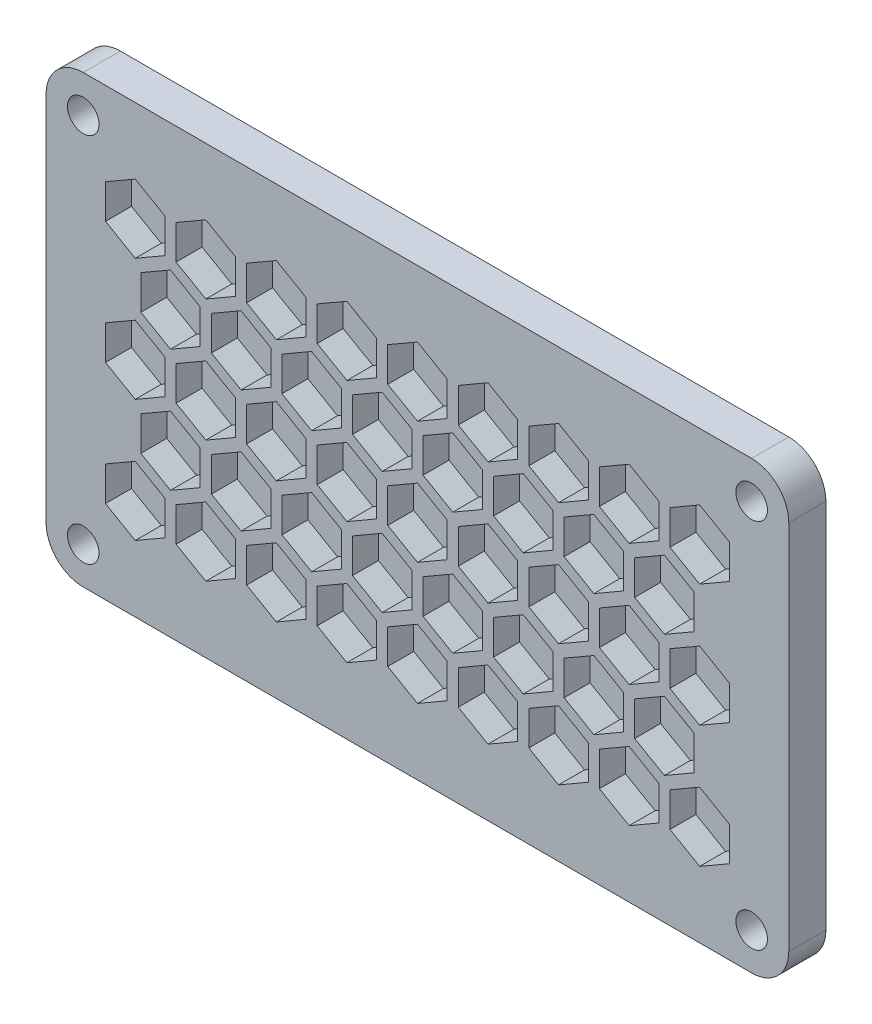
SolidWorks part; units mm, degrees
ref_plane "前视基准面" through (0, 0, 0) normal (0, 0, 1) x (1, 0, 0)
ref_plane "上视基准面" through (0, 0, 0) normal (0, 1, 0) x (1, 0, 0)
ref_plane "右视基准面" through (0, 0, 0) normal (1, 0, 0) x (0, 0, -1)
sketch "草图1" plane through (0, 0, 0) normal (0, 0, 1) x (1, 0, 0)
  line L0 (-90, -60) -> (90, -60)
  line L1 (100, -50) -> (100, 50)
  line L2 (90, 60) -> (-90, 60)
  line L3 (-100, 50) -> (-100, -50)
  arc A0 (-100, -50) -> (-90, -60) centre (-90, -50) ccw
  arc A1 (90, -60) -> (100, -50) centre (90, -50) ccw
  arc A2 (100, 50) -> (90, 60) centre (90, 50) ccw
  arc A3 (-90, 60) -> (-100, 50) centre (-90, 50) ccw
extrude "凸台-拉伸1" add sketch "草图1" along normal blind 10
ref_plane "基准面1" through (0, 0, 10) normal (0, 0, 1) x (1, 0, 0)
sketch "草图2" plane through (0, 0, 10) normal (0, 0, 1) x (1, 0, 0)
  line L0 (0, 9.2376) -> (-8, 4.6188)
  line L1 (-8, 4.6188) -> (-8, -4.6188)
  line L2 (-8, -4.6188) -> (0, -9.2376)
  line L3 (0, -9.2376) -> (8, -4.6188)
  line L4 (8, -4.6188) -> (8, 4.6188)
  line L5 (8, 4.6188) -> (0, 9.2376)
  line L6 (19, 9.2376) -> (11, 4.6188)
  line L7 (11, 4.6188) -> (11, -4.6188)
  line L8 (11, -4.6188) -> (19, -9.2376)
  line L9 (19, -9.2376) -> (27, -4.6188)
  line L10 (27, -4.6188) -> (27, 4.6188)
  line L11 (27, 4.6188) -> (19, 9.2376)
  line L12 (-19, 9.2376) -> (-27, 4.6188)
  line L13 (-27, 4.6188) -> (-27, -4.6188)
  line L14 (-27, -4.6188) -> (-19, -9.2376)
  line L15 (-19, -9.2376) -> (-11, -4.6188)
  line L16 (-11, -4.6188) -> (-11, 4.6188)
  line L17 (-11, 4.6188) -> (-19, 9.2376)
  line L18 (38, 9.2376) -> (30, 4.6188)
  line L19 (30, 4.6188) -> (30, -4.6188)
  line L20 (30, -4.6188) -> (38, -9.2376)
  line L21 (38, -9.2376) -> (46, -4.6188)
  line L22 (46, -4.6188) -> (46, 4.6188)
  line L23 (46, 4.6188) -> (38, 9.2376)
  line L24 (-38, 9.2376) -> (-46, 4.6188)
  line L25 (-46, 4.6188) -> (-46, -4.6188)
  line L26 (-46, -4.6188) -> (-38, -9.2376)
  line L27 (-38, -9.2376) -> (-30, -4.6188)
  line L28 (-30, -4.6188) -> (-30, 4.6188)
  line L29 (-30, 4.6188) -> (-38, 9.2376)
  line L30 (57, 9.2376) -> (49, 4.6188)
  line L31 (49, 4.6188) -> (49, -4.6188)
  line L32 (49, -4.6188) -> (57, -9.2376)
  line L33 (57, -9.2376) -> (65, -4.6188)
  line L34 (65, -4.6188) -> (65, 4.6188)
  line L35 (65, 4.6188) -> (57, 9.2376)
  line L36 (-57, 9.2376) -> (-65, 4.6188)
  line L37 (-65, 4.6188) -> (-65, -4.6188)
  line L38 (-65, -4.6188) -> (-57, -9.2376)
  line L39 (-57, -9.2376) -> (-49, -4.6188)
  line L40 (-49, -4.6188) -> (-49, 4.6188)
  line L41 (-49, 4.6188) -> (-57, 9.2376)
  line L42 (76, 9.2376) -> (68, 4.6188)
  line L43 (68, 4.6188) -> (68, -4.6188)
  line L44 (68, -4.6188) -> (76, -9.2376)
  line L45 (76, -9.2376) -> (84, -4.6188)
  line L46 (84, -4.6188) -> (84, 4.6188)
  line L47 (84, 4.6188) -> (76, 9.2376)
  line L48 (-76, 9.2376) -> (-84, 4.6188)
  line L49 (-84, 4.6188) -> (-84, -4.6188)
  line L50 (-84, -4.6188) -> (-76, -9.2376)
  line L51 (-76, -9.2376) -> (-68, -4.6188)
  line L52 (-68, -4.6188) -> (-68, 4.6188)
  line L53 (-68, 4.6188) -> (-76, 9.2376)
extrude "切除-拉伸1" cut sketch "草图2" against normal blind 7
sketch "草图3" plane through (0, 0, 10) normal (0, 0, 1) x (1, 0, 0)
  line L0 (9.5, 25.6916) -> (1.5, 21.0728)
  line L1 (1.5, 21.0728) -> (1.5, 11.8352)
  line L2 (1.5, 11.8352) -> (9.5, 7.2164)
  line L3 (9.5, 7.2164) -> (17.5, 11.8352)
  line L4 (17.5, 11.8352) -> (17.5, 21.0728)
  line L5 (17.5, 21.0728) -> (9.5, 25.6916)
  line L6 (-9.5, 25.6916) -> (-17.5, 21.0728)
  line L7 (-17.5, 21.0728) -> (-17.5, 11.8352)
  line L8 (-17.5, 11.8352) -> (-9.5, 7.2164)
  line L9 (-9.5, 7.2164) -> (-1.5, 11.8352)
  line L10 (-1.5, 11.8352) -> (-1.5, 21.0728)
  line L11 (-1.5, 21.0728) -> (-9.5, 25.6916)
  line L12 (28.5, 25.6916) -> (20.5, 21.0728)
  line L13 (20.5, 21.0728) -> (20.5, 11.8352)
  line L14 (20.5, 11.8352) -> (28.5, 7.2164)
  line L15 (28.5, 7.2164) -> (36.5, 11.8352)
  line L16 (36.5, 11.8352) -> (36.5, 21.0728)
  line L17 (36.5, 21.0728) -> (28.5, 25.6916)
  line L18 (-28.5, 25.6916) -> (-36.5, 21.0728)
  line L19 (-36.5, 21.0728) -> (-36.5, 11.8352)
  line L20 (-36.5, 11.8352) -> (-28.5, 7.2164)
  line L21 (-28.5, 7.2164) -> (-20.5, 11.8352)
  line L22 (-20.5, 11.8352) -> (-20.5, 21.0728)
  line L23 (-20.5, 21.0728) -> (-28.5, 25.6916)
  line L24 (47.5, 25.6916) -> (39.5, 21.0728)
  line L25 (39.5, 21.0728) -> (39.5, 11.8352)
  line L26 (39.5, 11.8352) -> (47.5, 7.2164)
  line L27 (47.5, 7.2164) -> (55.5, 11.8352)
  line L28 (55.5, 11.8352) -> (55.5, 21.0728)
  line L29 (55.5, 21.0728) -> (47.5, 25.6916)
  line L30 (-47.5, 25.6916) -> (-55.5, 21.0728)
  line L31 (-55.5, 21.0728) -> (-55.5, 11.8352)
  line L32 (-55.5, 11.8352) -> (-47.5, 7.2164)
  line L33 (-47.5, 7.2164) -> (-39.5, 11.8352)
  line L34 (-39.5, 11.8352) -> (-39.5, 21.0728)
  line L35 (-39.5, 21.0728) -> (-47.5, 25.6916)
  line L36 (66.5, 25.6916) -> (58.5, 21.0728)
  line L37 (58.5, 21.0728) -> (58.5, 11.8352)
  line L38 (58.5, 11.8352) -> (66.5, 7.2164)
  line L39 (66.5, 7.2164) -> (74.5, 11.8352)
  line L40 (74.5, 11.8352) -> (74.5, 21.0728)
  line L41 (74.5, 21.0728) -> (66.5, 25.6916)
  line L42 (-66.5, 25.6916) -> (-74.5, 21.0728)
  line L43 (-74.5, 21.0728) -> (-74.5, 11.8352)
  line L44 (-74.5, 11.8352) -> (-66.5, 7.2164)
  line L45 (-66.5, 7.2164) -> (-58.5, 11.8352)
  line L46 (-58.5, 11.8352) -> (-58.5, 21.0728)
  line L47 (-58.5, 21.0728) -> (-66.5, 25.6916)
  line L48 (9.5, -7.2164) -> (1.5, -11.8352)
  line L49 (1.5, -11.8352) -> (1.5, -21.0728)
  line L50 (1.5, -21.0728) -> (9.5, -25.6916)
  line L51 (9.5, -25.6916) -> (17.5, -21.0728)
  line L52 (17.5, -21.0728) -> (17.5, -11.8352)
  line L53 (17.5, -11.8352) -> (9.5, -7.2164)
  line L54 (-9.5, -7.2164) -> (-17.5, -11.8352)
  line L55 (-17.5, -11.8352) -> (-17.5, -21.0728)
  line L56 (-17.5, -21.0728) -> (-9.5, -25.6916)
  line L57 (-9.5, -25.6916) -> (-1.5, -21.0728)
  line L58 (-1.5, -21.0728) -> (-1.5, -11.8352)
  line L59 (-1.5, -11.8352) -> (-9.5, -7.2164)
  line L60 (28.5, -7.2164) -> (20.5, -11.8352)
  line L61 (20.5, -11.8352) -> (20.5, -21.0728)
  line L62 (20.5, -21.0728) -> (28.5, -25.6916)
  line L63 (28.5, -25.6916) -> (36.5, -21.0728)
  line L64 (36.5, -21.0728) -> (36.5, -11.8352)
  line L65 (36.5, -11.8352) -> (28.5, -7.2164)
  line L66 (-28.5, -7.2164) -> (-36.5, -11.8352)
  line L67 (-36.5, -11.8352) -> (-36.5, -21.0728)
  line L68 (-36.5, -21.0728) -> (-28.5, -25.6916)
  line L69 (-28.5, -25.6916) -> (-20.5, -21.0728)
  line L70 (-20.5, -21.0728) -> (-20.5, -11.8352)
  line L71 (-20.5, -11.8352) -> (-28.5, -7.2164)
  line L72 (47.5, -7.2164) -> (39.5, -11.8352)
  line L73 (39.5, -11.8352) -> (39.5, -21.0728)
  line L74 (39.5, -21.0728) -> (47.5, -25.6916)
  line L75 (47.5, -25.6916) -> (55.5, -21.0728)
  line L76 (55.5, -21.0728) -> (55.5, -11.8352)
  line L77 (55.5, -11.8352) -> (47.5, -7.2164)
  line L78 (-47.5, -7.2164) -> (-55.5, -11.8352)
  line L79 (-55.5, -11.8352) -> (-55.5, -21.0728)
  line L80 (-55.5, -21.0728) -> (-47.5, -25.6916)
  line L81 (-47.5, -25.6916) -> (-39.5, -21.0728)
  line L82 (-39.5, -21.0728) -> (-39.5, -11.8352)
  line L83 (-39.5, -11.8352) -> (-47.5, -7.2164)
  line L84 (66.5, -7.2164) -> (58.5, -11.8352)
  line L85 (58.5, -11.8352) -> (58.5, -21.0728)
  line L86 (58.5, -21.0728) -> (66.5, -25.6916)
  line L87 (66.5, -25.6916) -> (74.5, -21.0728)
  line L88 (74.5, -21.0728) -> (74.5, -11.8352)
  line L89 (74.5, -11.8352) -> (66.5, -7.2164)
  line L90 (-66.5, -7.2164) -> (-74.5, -11.8352)
  line L91 (-74.5, -11.8352) -> (-74.5, -21.0728)
  line L92 (-74.5, -21.0728) -> (-66.5, -25.6916)
  line L93 (-66.5, -25.6916) -> (-58.5, -21.0728)
  line L94 (-58.5, -21.0728) -> (-58.5, -11.8352)
  line L95 (-58.5, -11.8352) -> (-66.5, -7.2164)
  line L96 (0, 42.1466) -> (-8, 37.5278)
  line L97 (-8, 37.5278) -> (-8, 28.2902)
  line L98 (-8, 28.2902) -> (0, 23.6714)
  line L99 (0, 23.6714) -> (8, 28.2902)
  line L100 (8, 28.2902) -> (8, 37.5278)
  line L101 (8, 37.5278) -> (0, 42.1466)
  line L102 (19, 42.1466) -> (11, 37.5278)
  line L103 (11, 37.5278) -> (11, 28.2902)
  line L104 (11, 28.2902) -> (19, 23.6714)
  line L105 (19, 23.6714) -> (27, 28.2902)
  line L106 (27, 28.2902) -> (27, 37.5278)
  line L107 (27, 37.5278) -> (19, 42.1466)
  line L108 (-19, 42.1466) -> (-27, 37.5278)
  line L109 (-27, 37.5278) -> (-27, 28.2902)
  line L110 (-27, 28.2902) -> (-19, 23.6714)
  line L111 (-19, 23.6714) -> (-11, 28.2902)
  line L112 (-11, 28.2902) -> (-11, 37.5278)
  line L113 (-11, 37.5278) -> (-19, 42.1466)
  line L114 (38, 42.1466) -> (30, 37.5278)
  line L115 (30, 37.5278) -> (30, 28.2902)
  line L116 (30, 28.2902) -> (38, 23.6714)
  line L117 (38, 23.6714) -> (46, 28.2902)
  line L118 (46, 28.2902) -> (46, 37.5278)
  line L119 (46, 37.5278) -> (38, 42.1466)
  line L120 (-38, 42.1466) -> (-46, 37.5278)
  line L121 (-46, 37.5278) -> (-46, 28.2902)
  line L122 (-46, 28.2902) -> (-38, 23.6714)
  line L123 (-38, 23.6714) -> (-30, 28.2902)
  line L124 (-30, 28.2902) -> (-30, 37.5278)
  line L125 (-30, 37.5278) -> (-38, 42.1466)
  line L126 (57, 42.1466) -> (49, 37.5278)
  line L127 (49, 37.5278) -> (49, 28.2902)
  line L128 (49, 28.2902) -> (57, 23.6714)
  line L129 (57, 23.6714) -> (65, 28.2902)
  line L130 (65, 28.2902) -> (65, 37.5278)
  line L131 (65, 37.5278) -> (57, 42.1466)
  line L132 (-57, 42.1466) -> (-65, 37.5278)
  line L133 (-65, 37.5278) -> (-65, 28.2902)
  line L134 (-65, 28.2902) -> (-57, 23.6714)
  line L135 (-57, 23.6714) -> (-49, 28.2902)
  line L136 (-49, 28.2902) -> (-49, 37.5278)
  line L137 (-49, 37.5278) -> (-57, 42.1466)
  line L138 (76, 42.1466) -> (68, 37.5278)
  line L139 (68, 37.5278) -> (68, 28.2902)
  line L140 (68, 28.2902) -> (76, 23.6714)
  line L141 (76, 23.6714) -> (84, 28.2902)
  line L142 (84, 28.2902) -> (84, 37.5278)
  line L143 (84, 37.5278) -> (76, 42.1466)
  line L144 (-76, 42.1466) -> (-84, 37.5278)
  line L145 (-84, 37.5278) -> (-84, 28.2902)
  line L146 (-84, 28.2902) -> (-76, 23.6714)
  line L147 (-76, 23.6714) -> (-68, 28.2902)
  line L148 (-68, 28.2902) -> (-68, 37.5278)
  line L149 (-68, 37.5278) -> (-76, 42.1466)
  line L150 (0, -23.6714) -> (-8, -28.2902)
  line L151 (-8, -28.2902) -> (-8, -37.5278)
  line L152 (-8, -37.5278) -> (0, -42.1466)
  line L153 (0, -42.1466) -> (8, -37.5278)
  line L154 (8, -37.5278) -> (8, -28.2902)
  line L155 (8, -28.2902) -> (0, -23.6714)
  line L156 (19, -23.6714) -> (11, -28.2902)
  line L157 (11, -28.2902) -> (11, -37.5278)
  line L158 (11, -37.5278) -> (19, -42.1466)
  line L159 (19, -42.1466) -> (27, -37.5278)
  line L160 (27, -37.5278) -> (27, -28.2902)
  line L161 (27, -28.2902) -> (19, -23.6714)
  line L162 (-19, -23.6714) -> (-27, -28.2902)
  line L163 (-27, -28.2902) -> (-27, -37.5278)
  line L164 (-27, -37.5278) -> (-19, -42.1466)
  line L165 (-19, -42.1466) -> (-11, -37.5278)
  line L166 (-11, -37.5278) -> (-11, -28.2902)
  line L167 (-11, -28.2902) -> (-19, -23.6714)
  line L168 (38, -23.6714) -> (30, -28.2902)
  line L169 (30, -28.2902) -> (30, -37.5278)
  line L170 (30, -37.5278) -> (38, -42.1466)
  line L171 (38, -42.1466) -> (46, -37.5278)
  line L172 (46, -37.5278) -> (46, -28.2902)
  line L173 (46, -28.2902) -> (38, -23.6714)
  line L174 (-38, -23.6714) -> (-46, -28.2902)
  line L175 (-46, -28.2902) -> (-46, -37.5278)
  line L176 (-46, -37.5278) -> (-38, -42.1466)
  line L177 (-38, -42.1466) -> (-30, -37.5278)
  line L178 (-30, -37.5278) -> (-30, -28.2902)
  line L179 (-30, -28.2902) -> (-38, -23.6714)
  line L180 (57, -23.6714) -> (49, -28.2902)
  line L181 (49, -28.2902) -> (49, -37.5278)
  line L182 (49, -37.5278) -> (57, -42.1466)
  line L183 (57, -42.1466) -> (65, -37.5278)
  line L184 (65, -37.5278) -> (65, -28.2902)
  line L185 (65, -28.2902) -> (57, -23.6714)
  line L186 (-57, -23.6714) -> (-65, -28.2902)
  line L187 (-65, -28.2902) -> (-65, -37.5278)
  line L188 (-65, -37.5278) -> (-57, -42.1466)
  line L189 (-57, -42.1466) -> (-49, -37.5278)
  line L190 (-49, -37.5278) -> (-49, -28.2902)
  line L191 (-49, -28.2902) -> (-57, -23.6714)
  line L192 (76, -23.6714) -> (68, -28.2902)
  line L193 (68, -28.2902) -> (68, -37.5278)
  line L194 (68, -37.5278) -> (76, -42.1466)
  line L195 (76, -42.1466) -> (84, -37.5278)
  line L196 (84, -37.5278) -> (84, -28.2902)
  line L197 (84, -28.2902) -> (76, -23.6714)
  line L198 (-76, -23.6714) -> (-84, -28.2902)
  line L199 (-84, -28.2902) -> (-84, -37.5278)
  line L200 (-84, -37.5278) -> (-76, -42.1466)
  line L201 (-76, -42.1466) -> (-68, -37.5278)
  line L202 (-68, -37.5278) -> (-68, -28.2902)
  line L203 (-68, -28.2902) -> (-76, -23.6714)
extrude "切除-拉伸2" cut sketch "草图3" against normal blind 7
sketch "草图4" plane through (0, 0, 10) normal (0, 0, 1) x (1, 0, 0)
  circle A0 centre (90, 50) radius 4.25
  circle A1 centre (90, -50) radius 4.25
  circle A2 centre (-90, 50) radius 4.25
  circle A3 centre (-90, -50) radius 4.25
extrude "切除-拉伸3" cut sketch "草图4" against normal through all
